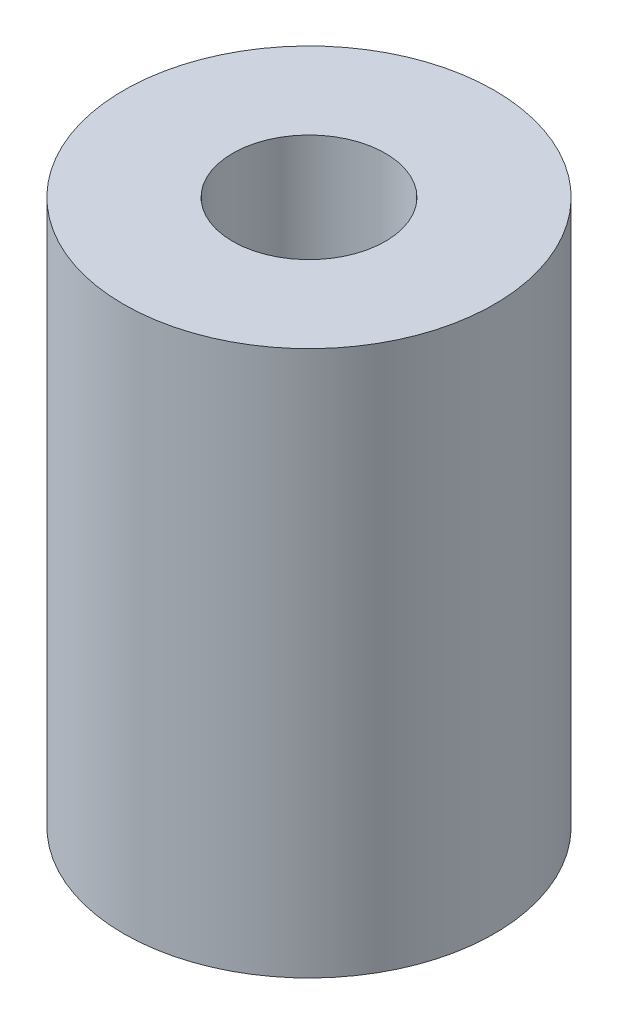
SolidWorks part; units mm, degrees
ref_plane "Front Plane" through (0, 0, 0) normal (0, 0, 1) x (1, 0, 0)
ref_plane "Top Plane" through (0, 0, 0) normal (0, 1, 0) x (1, 0, 0)
ref_plane "Right Plane" through (0, 0, 0) normal (1, 0, 0) x (0, 0, -1)
sketch "Sketch1" plane through (0, 0, 0) normal (0, 1, 0) x (1, 0, 0)
  circle A0 centre (0, 0) radius 5.1016
  circle A1 centre (0, 0) radius 2.1016
  dimension "D1" = 4.2032
  dimension "D2" = 3
extrude "Boss-Extrude1" add sketch "Sketch1" along normal blind 15
